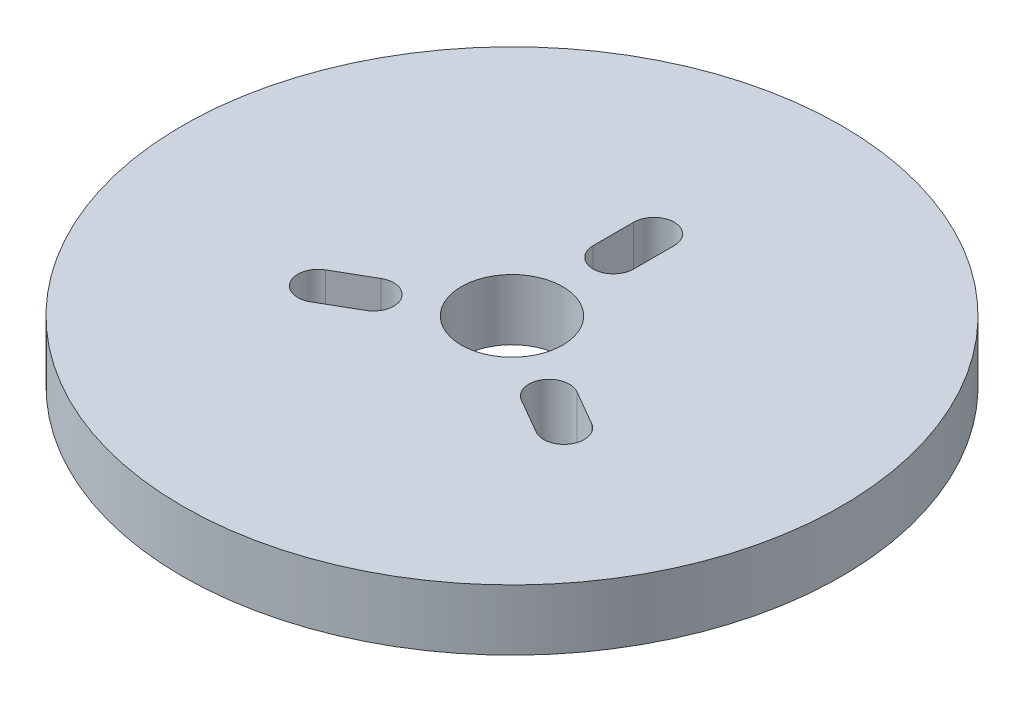
SolidWorks part; units mm, degrees
ref_plane "前视基准面" through (0, 0, 0) normal (0, 0, 1) x (1, 0, 0)
ref_plane "上视基准面" through (0, 0, 0) normal (0, 1, 0) x (1, 0, 0)
ref_plane "右视基准面" through (0, 0, 0) normal (1, 0, 0) x (0, 0, -1)
sketch "Sketch1" plane through (0, 0, 0) normal (0, 1, 0) x (1, 0, 0)
  line L0 (0, 10) -> (0, 14) construction
  line L1 (-2, 10) -> (-2, 14)
  line L2 (2, 10) -> (2, 14)
  line L3 (8.6603, -5) -> (12.1244, -7) construction
  line L4 (9.6603, -3.2679) -> (13.1244, -5.2679)
  line L5 (7.6603, -6.7321) -> (11.1244, -8.7321)
  line L6 (-8.6603, -5) -> (-12.1244, -7) construction
  line L7 (-7.6603, -6.7321) -> (-11.1244, -8.7321)
  line L8 (-9.6603, -3.2679) -> (-13.1244, -5.2679)
  circle A0 centre (0, 0) radius 32.5
  circle A1 centre (0, 0) radius 5
  arc A2 (-2, 10) -> (2, 10) centre (0, 10) ccw
  arc A3 (2, 14) -> (-2, 14) centre (0, 14) ccw
  arc A4 (9.6603, -3.2679) -> (7.6603, -6.7321) centre (8.6603, -5) ccw
  arc A5 (11.1244, -8.7321) -> (13.1244, -5.2679) centre (12.1244, -7) ccw
  arc A6 (-7.6603, -6.7321) -> (-9.6603, -3.2679) centre (-8.6603, -5) ccw
  arc A7 (-13.1244, -5.2679) -> (-11.1244, -8.7321) centre (-12.1244, -7) ccw
  point P6 (0, 12)
  point P11 (0, 8)
  point P16 (10.3923, -6)
  point P23 (-10.3923, -6)
  point P28 (0, 0)
  dimension "D1" = 65
  dimension "D2" = 10
  dimension "D4" = 2
  dimension "D5" = 8
  dimension "D3" = 4
  dimension "D6" = 3
extrude "Boss-Extrude1" add sketch "Sketch1" along normal blind 6
